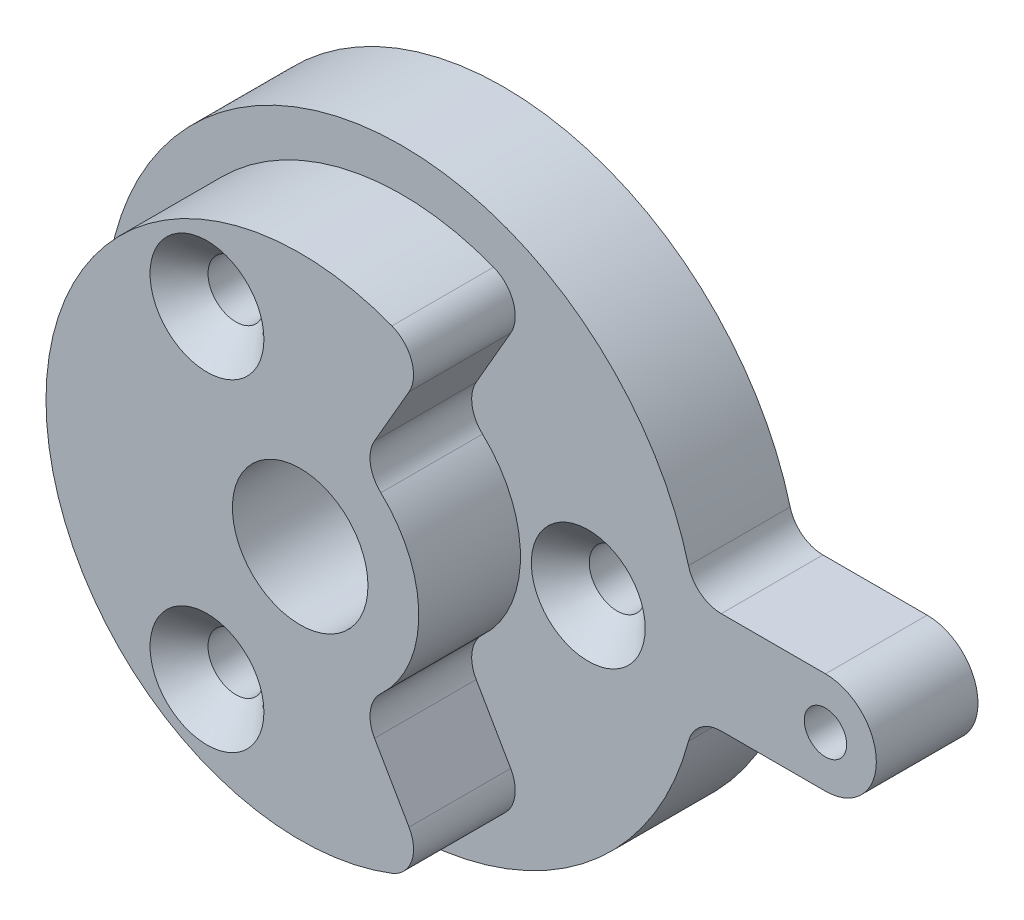
SolidWorks part; units mm, degrees
material "5052-O"
ref_plane "Front Plane" through (0, 0, 0) normal (0, 0, 1) x (1, 0, 0)
ref_plane "Top Plane" through (0, 0, 0) normal (0, 1, 0) x (1, 0, 0)
ref_plane "Right Plane" through (0, 0, 0) normal (1, 0, 0) x (0, 0, -1)
sketch "Sketch1" plane through (0, 0, 0) normal (0, 0, 1) x (1, 0, 0)
  circle A0 centre (0, 0) radius 35
  circle A1 centre (0, 0) radius 8
  dimension "D1" = 70
  dimension "D2" = 16
extrude "Boss-Extrude1" add sketch "Sketch1" along normal blind 12
sketch "Sketch2" plane through (0, 0, 12) normal (0, 0, 1) x (1, 0, 0)
  line L0 (15, 25.9808) -> (7, 12.1244)
  line L1 (7, -12.1244) -> (15, -25.9808)
  line L2 (0, 0) -> (14, 0) construction
  arc A0 (15, 25.9808) -> (15, -25.9808) centre (0, 0) ccw
  circle A3 centre (0, 0) radius 8 construction
  circle A4 centre (0, 0) radius 8
  arc A6 (7, -12.1244) -> (7, 12.1244) centre (0, 0) ccw
  circle A7 centre (0, 0) radius 14 construction
  point P6 (8.2358, -29.3138)
  point P7 (23.2431, 18.9672)
  dimension "D2" = 60
  dimension "D3" = 120
  dimension "D1" = 6
extrude "Boss-Extrude2" add sketch "Sketch2" along normal blind 12
sketch "Sketch5" plane through (0, 0, 12) normal (0, 0, 1) x (1, 0, 0)
  line L0 (50, 0) -> (14, 0) construction
  line L1 (50, -6) -> (14, -6)
  line L2 (50, 6) -> (14, 6)
  arc A1 (50, -6) -> (50, 6) centre (50, 0) ccw
  arc A2 (14, 6) -> (14, -6) centre (14, 0) ccw
  arc A3 (7, -12.1244) -> (7, 12.1244) centre (0, 0) ccw construction
  point P3 (27.0598, 0)
  point P4 (19, 0)
  point P6 (32, 0)
  point P11 (35, 0)
  dimension "D1" = 12
  dimension "D2" = 50
extrude "Boss-Extrude3" add sketch "Sketch5" against normal up to surface (12 mm away) up to face at (35, 0, 0)
fillet "Fillet1" radius 4 6 edges at (7, -12.1244, 18) (15, -25.9808, 18) (15, 25.9808, 18) (7, 12.1244, 18) (34.4819, -6, 6) (34.4819, 6, 6)
hole_wizard "M6 Tapped Hole1" positions "Sketch6" profile "Sketch7" tap size "M6" standard "ISO" end condition through all
sketch "Sketch6" plane through (0, 0, 12) normal (0, 0, 1) x (1, 0, 0)
  point P0 (50, 0)
sketch "Sketch7" plane through (50, 0, 12) normal (1, 0, 0) x (0, -1, 0)
  line L0 (0, 0) -> (0, 12)
  line L1 (0, 12) -> (2.5, 12)
  line L2 (2.5, 12) -> (2.5, 0)
  line L5 (2.5, 0) -> (0, 0)
  line L11 (0, -6.35) -> (0, 107.95) construction
  dimension "Thru Tap Drill Dia." = 5
  dimension "Thru Tap Drill Depth" = 12
cosmetic thread "Hole Thread1" parameters "D2"=6
hole_wizard "CSK for M6 Hex Socket Countersunk Cap Screw1" positions "3DSketch1" profile "Sketch8" countersink size "M6" standard "ISO" end condition through all
sketch3d "3DSketch1"
  line L0 (0, 0, 0) -> (0, 0, 24) construction
  line L1 (0, 0, 24) -> (0, 0, 12) construction
  line L3 (0, 0, 24) -> (0, 0, 12) construction
  line L4 (0, 0, 24) -> (0, 0, 0) construction
  line L5 (0, 0, 12) -> (22, 0, 12) construction
  line L7 (-11, 19.0526, 24) -> (0, 0, 24) construction
  line L8 (0, 0, 24) -> (-11, -19.0526, 24) construction
  point P0 (-11, 19.0526, 24)
  point P2 (-11, -19.0526, 24)
  point P4 (22, 0, 12)
  point P25 (0, 0, 0)
  point P26 (-16.7447, 17.1935, 24)
  dimension "D1" = 22
  dimension "D2" = 22
  dimension "D3" = 120
sketch "Sketch8" plane through (-11, 19.0526, 24) normal (1, 0, 0) x (0, -1, 0)
  line L0 (0, 0) -> (0, 24)
  line L1 (0, 24) -> (3.3, 24)
  line L2 (3.3, 24) -> (3.3, 3.42)
  line L3 (3.3, 3.42) -> (6.72, 0)
  line L5 (6.72, 0) -> (0, 0)
  line L6 (-3.3, 3.42) -> (-6.72, 0) construction
  line L11 (0, -6.35) -> (0, 107.95) construction
  dimension "Thru Hole Dia." = 6.6
  dimension "Thru Hole Depth" = 24
  dimension "Near C'Sink Dia." = 13.44
  dimension "Near C'Sink Angle" = 90
